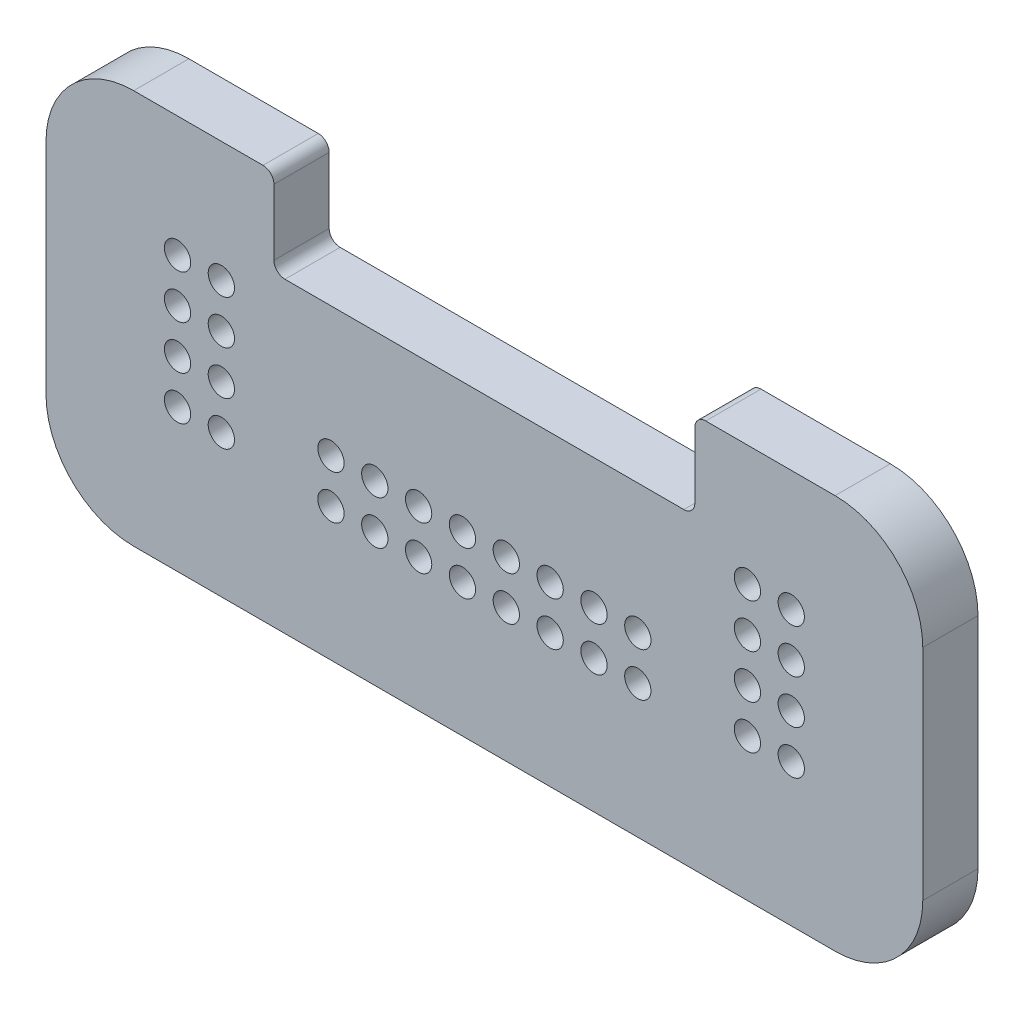
SolidWorks part; units mm, degrees
ref_plane "Front Plane" through (0, 0, 0) normal (0, 0, 1) x (1, 0, 0)
ref_plane "Top Plane" through (0, 0, 0) normal (0, 1, 0) x (1, 0, 0)
ref_plane "Right Plane" through (0, 0, 0) normal (1, 0, 0) x (0, 0, -1)
sketch "Sketch1" plane through (0, 0, -31.8411) normal (0, 0, -1) x (-1, 0, 0)
  line L0 (12.573, -7.3025) -> (-12.573, -7.3025) construction
  line L1 (10.16, 5.3975) -> (-10.16, 5.3975)
  line L2 (12.7, 2.8575) -> (12.7, -3.4925)
  line L3 (10.16, -6.0325) -> (-10.16, -6.0325)
  line L4 (-12.7, 2.8575) -> (-12.7, -3.4925)
  line L5 (12.7, 5.3975) -> (-12.7, -6.0325) construction
  line L6 (12.7, -6.0325) -> (-12.7, 5.3975) construction
  line L7 (-5.0419, 2.8575) -> (5.0419, 2.8575) construction
  arc A0 (-10.16, 5.3975) -> (-12.7, 2.8575) centre (-10.16, 2.8575) ccw
  arc A1 (-10.16, -6.0325) -> (-12.7, -3.4925) centre (-10.16, -3.4925) cw
  arc A2 (12.7, -3.4925) -> (10.16, -6.0325) centre (10.16, -3.4925) cw
  arc A3 (10.16, 5.3975) -> (12.7, 2.8575) centre (10.16, 2.8575) cw
  point P0 (0, -0.3175)
  dimension "D4" = 2.54
  dimension "D1" = 25.4
  dimension "D2" = 1.27
  dimension "D3" = 2.54
extrude "Boss-Extrude1" add sketch "Sketch1" along normal blind 1.6
sketch "Sketch2" plane through (0, 0, -31.8411) normal (0, 0, 1) x (1, 0, 0)
  line L0 (-5.7785, 2.8575) -> (5.7785, 2.8575)
  line L1 (-5.0419, 2.8575) -> (5.0419, 2.8575) construction
  line L2 (-6.096, 3.175) -> (-6.096, 5.08)
  line L3 (-10.16, 5.3975) -> (10.16, 5.3975) construction
  line L4 (6.096, 3.175) -> (6.096, 5.08)
  line L5 (-6.4135, 5.3975) -> (6.4135, 5.3975)
  line L6 (0, -18.9136) -> (0, 18.9136) construction
  arc A0 (-6.096, 5.08) -> (-6.4135, 5.3975) centre (-6.4135, 5.08) ccw
  arc A1 (-5.7785, 2.8575) -> (-6.096, 3.175) centre (-5.7785, 3.175) cw
  arc A2 (5.7785, 2.8575) -> (6.096, 3.175) centre (5.7785, 3.175) ccw
  arc A3 (6.096, 5.08) -> (6.4135, 5.3975) centre (6.4135, 5.08) cw
  point P2 (0, 2.8575)
  dimension "D1" = 0.3175
  dimension "D2" = 12.192
extrude "Cut-Extrude1" cut sketch "Sketch2" against normal through all
sketch "Sketch3" plane through (0, 0, -31.8411) normal (0, 0, 1) x (1, 0, 0)
  line L1 (-7.874, 2.159) -> (-7.366, 1.651) construction
  line L2 (-9.144, -1.651) -> (-8.636, -2.159) construction
  line L3 (0, -0.88) -> (0, 0.88) construction
  line L4 (4.2418, -1.9685) -> (4.6482, -2.3749) construction
  circle A0 centre (-7.62, 1.905) radius 0.381
  circle A1 centre (-8.89, 1.905) radius 0.381
  circle A2 centre (-8.89, 0.635) radius 0.381
  circle A3 centre (-8.89, -0.635) radius 0.381
  circle A4 centre (-8.89, -1.905) radius 0.381
  circle A5 centre (-7.62, 0.635) radius 0.381
  circle A6 centre (-7.62, -0.635) radius 0.381
  circle A7 centre (-7.62, -1.905) radius 0.381
  circle A8 centre (8.89, -0.635) radius 0.381
  circle A9 centre (8.89, -1.905) radius 0.381
  circle A10 centre (7.62, -1.905) radius 0.381
  circle A11 centre (7.62, -0.635) radius 0.381
  circle A12 centre (7.62, 1.905) radius 0.381
  circle A13 centre (7.62, 0.635) radius 0.381
  circle A14 centre (8.89, 0.635) radius 0.381
  circle A15 centre (8.89, 1.905) radius 0.381
  circle A16 centre (4.445, -2.1717) radius 0.381
  circle A17 centre (3.175, -2.1717) radius 0.381
  circle A18 centre (1.905, -2.1717) radius 0.381
  circle A19 centre (0.635, -2.1717) radius 0.381
  circle A20 centre (-0.635, -2.1717) radius 0.381
  circle A21 centre (-1.905, -2.1717) radius 0.381
  circle A22 centre (-3.175, -2.1717) radius 0.381
  circle A23 centre (-4.445, -2.1717) radius 0.381
  circle A24 centre (3.175, -0.9017) radius 0.381
  circle A25 centre (1.905, -0.9017) radius 0.381
  circle A26 centre (0.635, -0.9017) radius 0.381
  circle A27 centre (-0.635, -0.9017) radius 0.381
  circle A28 centre (-1.905, -0.9017) radius 0.381
  circle A29 centre (-3.175, -0.9017) radius 0.381
  circle A30 centre (-4.445, -0.9017) radius 0.381
  circle A31 centre (4.445, -0.9017) radius 0.381
  dimension "D1" = 0.762
  dimension "D6" = 1.27
  dimension "D7" = 1.27
  dimension "D2" = 2
  dimension "D3" = 4
  dimension "D4" = 8
  dimension "D5" = 2
extrude "Cut-Extrude2" cut sketch "Sketch3" against normal through all
sketch "Sketch4" plane through (0, 0, -31.8411) normal (0, 0, 1) x (1, 0, 0)
  line L16 (-6.096, 3.175) -> (-6.096, 5.08)
  line L17 (-6.4135, 5.3975) -> (-10.16, 5.3975)
  line L18 (-12.7, 2.8575) -> (-12.7, -3.4925)
  line L19 (-10.16, -6.0325) -> (10.16, -6.0325)
  line L20 (12.7, -3.4925) -> (12.7, 2.8575)
  line L21 (10.16, 5.3975) -> (6.4135, 5.3975)
  line L22 (6.096, 5.08) -> (6.096, 3.175)
  line L23 (5.7785, 2.8575) -> (-5.7785, 2.8575)
  line L24 (-6.096, 3.175) -> (-6.096, 5.08)
  line L25 (-6.4135, 5.3975) -> (-10.16, 5.3975)
  line L26 (-12.7, 2.8575) -> (-12.7, -3.4925)
  line L27 (-10.16, -6.0325) -> (10.16, -6.0325)
  line L28 (12.7, -3.4925) -> (12.7, 2.8575)
  line L29 (10.16, 5.3975) -> (6.4135, 5.3975)
  line L30 (6.096, 5.08) -> (6.096, 3.175)
  line L31 (5.7785, 2.8575) -> (-5.7785, 2.8575)
  arc A16 (-6.096, 5.08) -> (-6.4135, 5.3975) centre (-6.4135, 5.08) ccw
  arc A17 (-10.16, 5.3975) -> (-12.7, 2.8575) centre (-10.16, 2.8575) ccw
  arc A18 (-12.7, -3.4925) -> (-10.16, -6.0325) centre (-10.16, -3.4925) ccw
  arc A19 (10.16, -6.0325) -> (12.7, -3.4925) centre (10.16, -3.4925) ccw
  arc A20 (12.7, 2.8575) -> (10.16, 5.3975) centre (10.16, 2.8575) ccw
  arc A21 (6.4135, 5.3975) -> (6.096, 5.08) centre (6.4135, 5.08) ccw
  arc A22 (5.7785, 2.8575) -> (6.096, 3.175) centre (5.7785, 3.175) ccw
  arc A23 (-6.096, 3.175) -> (-5.7785, 2.8575) centre (-5.7785, 3.175) ccw
  arc A24 (-6.096, 5.08) -> (-6.4135, 5.3975) centre (-6.4135, 5.08) ccw
  arc A25 (-10.16, 5.3975) -> (-12.7, 2.8575) centre (-10.16, 2.8575) ccw
  arc A26 (-12.7, -3.4925) -> (-10.16, -6.0325) centre (-10.16, -3.4925) ccw
  arc A27 (10.16, -6.0325) -> (12.7, -3.4925) centre (10.16, -3.4925) ccw
  arc A28 (12.7, 2.8575) -> (10.16, 5.3975) centre (10.16, 2.8575) ccw
  arc A29 (6.4135, 5.3975) -> (6.096, 5.08) centre (6.4135, 5.08) ccw
  arc A30 (5.7785, 2.8575) -> (6.096, 3.175) centre (5.7785, 3.175) ccw
  arc A31 (-6.096, 3.175) -> (-5.7785, 2.8575) centre (-5.7785, 3.175) ccw
  point P2 (-8.89, 1.905)
  point P12 (8.89, -1.905)
  point P32 (-4.445, -0.9017)
  dimension "D2" = 1.905
  dimension "D3" = 8.89
  dimension "D4" = 3.4925
  dimension "D1" = 0
